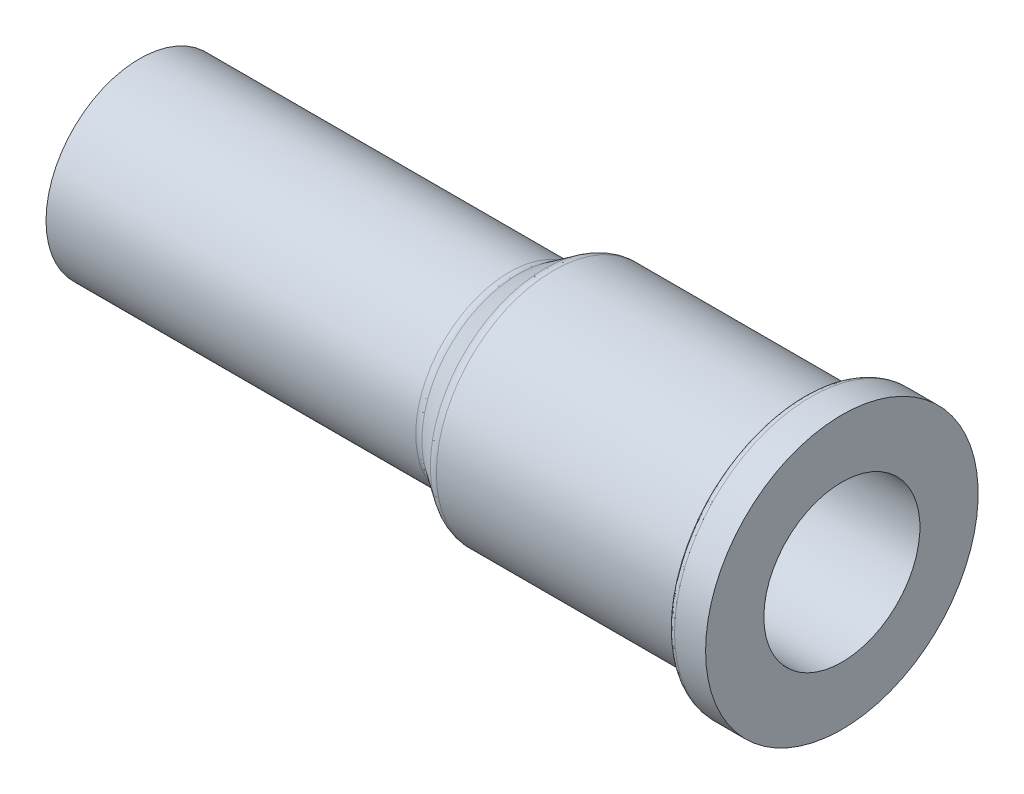
SolidWorks part; units mm, degrees
ref_plane "前视基准面" through (0, 0, 0) normal (0, 0, 1) x (1, 0, 0)
ref_plane "上视基准面" through (0, 0, 0) normal (0, 1, 0) x (1, 0, 0)
ref_plane "右视基准面" through (0, 0, 0) normal (1, 0, 0) x (0, 0, -1)
sketch "草图2" plane through (0, 0, 0) normal (0, 0, 1) x (1, 0, 0)
  line L0 (-59.1358, 0) -> (63.985, 0) construction
  line L1 (-32.842, 5) -> (12.158, 5)
  line L2 (12.158, 5) -> (12.158, 7.5)
  line L3 (-8.842, 6) -> (-6.6336, 7.5)
  line L4 (9.3664, 7.5) -> (9.8152, 8.7329)
  line L5 (9.3664, 7.5) -> (-6.6336, 7.5)
  line L6 (9.8152, 8.7329) -> (12.158, 8.7329)
  line L7 (-8.842, 6) -> (-32.842, 6)
  line L8 (-32.842, 6) -> (-32.842, 5)
  line L9 (12.158, 8.7329) -> (12.158, 7.5)
  dimension "D1" = 5
  dimension "D2" = 6
  dimension "D4" = 45
  dimension "D5" = 24
  dimension "D6" = 16
  dimension "D8" = 2.3428
revolve "旋转1" add sketch "草图2" angle 360 about L0
fillet "圆角2" radius 0.5 1 edges at (9.3664, 0, 7.5)
fillet "圆角3" radius 0.5 1 edges at (9.8152, 0, 8.7329)
fillet "圆角4" radius 1 1 edges at (-6.6336, 0, 7.5)
fillet "圆角5" radius 1 1 edges at (-8.842, 0, 6)
